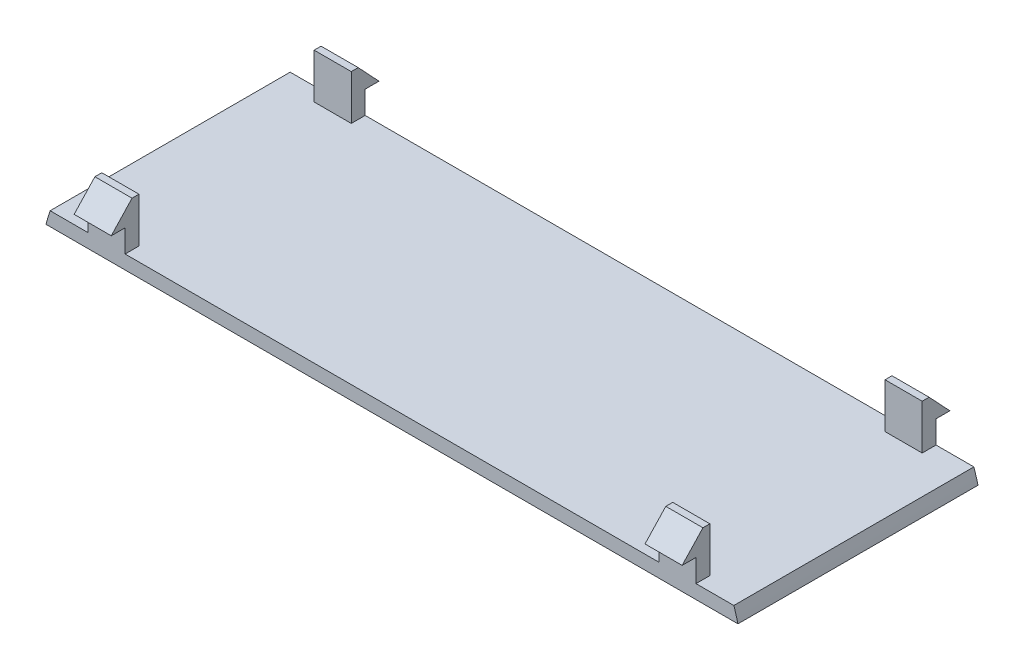
SolidWorks part; units mm, degrees
ref_plane "Front Plane" through (0, 0, 0) normal (0, 0, 1) x (1, 0, 0)
ref_plane "Top Plane" through (0, 0, 0) normal (0, 1, 0) x (1, 0, 0)
ref_plane "Right Plane" through (0, 0, 0) normal (1, 0, 0) x (0, 0, -1)
sketch "Sketch1" plane through (0, 0, 0) normal (0, 0, 1) x (1, 0, 0)
  line L0 (0, 0) -> (-79.2763, 0)
  line L1 (-78.8038, 1.5875) -> (-0.4724, 1.5875)
  line L2 (-39.6381, 0) -> (-39.6381, 1.5875) construction
  arc A0 (-79.2763, 0) -> (-78.8038, 1.5875) centre (-56.2306, -5.9944) cw
  arc A1 (-0.4724, 1.5875) -> (0, 0) centre (-23.0457, -5.9944) cw
  point P9 (0, 0)
  dimension "D1" = 1.5875
extrude "Boss-Extrude1" add sketch "Sketch1" along normal blind 27.5
sketch3d "3DSketch1"
  line L1 (-0.4724, 1.5875, 27.5) -> (-78.8038, 1.5875, 27.5) construction
  line L2 (-4.8084, 1.5875, 27.5) -> (-4.8084, 4.191, 27.5)
  line L3 (-4.8084, 4.191, 27.5) -> (-4.8084, 4.191, 29.0875)
  line L4 (-4.8084, 4.191, 29.0875) -> (-4.8084, 6.731, 26.7062)
  line L5 (-4.8084, 6.731, 26.7062) -> (-4.8084, 6.731, 25.9125)
  line L6 (-4.8084, 6.731, 25.9125) -> (-4.8084, 1.5875, 25.9125)
  line L7 (-4.8084, 1.5875, 25.9125) -> (-4.8084, 1.5875, 27.5)
  line L8 (-4.8084, 4.191, 27.5) -> (-4.8084, 6.223, 27.5) construction
  line L9 (-39.6381, 1.5875, 27.5) -> (-4.8084, 1.5875, 27.5) construction
  point P5 (-39.6381, 1.5875, 27.5)
  point P11 (-39.6381, 1.5875, 27.5)
  dimension "D2" = 34.8297
  dimension "D3" = 2.6035
  dimension "D4" = 1.5875
  dimension "D5" = 2.54
  dimension "D6" = 2.032
  dimension "D7" = 0.7937
  dimension "D8" = 1.5875
extrude "Boss-Extrude2" add sketch "3DSketch1" along direction (-1, 0, 0) on the side against the normal blind 4.2545 contours L2 L3 L4 L5 L6 L7
pattern_linear "LPattern2" count 2 spacing 65.405 along (-1, 0, 0) of "Boss-Extrude2"
ref_plane "Plane1" through (0, 0, 13.75) normal (0, 0, 1) x (1, 0, 0)
mirror "Mirror2" about plane through (0, 0, 13.75) normal (0, 0, 1) of "LPattern2", "Boss-Extrude2"
